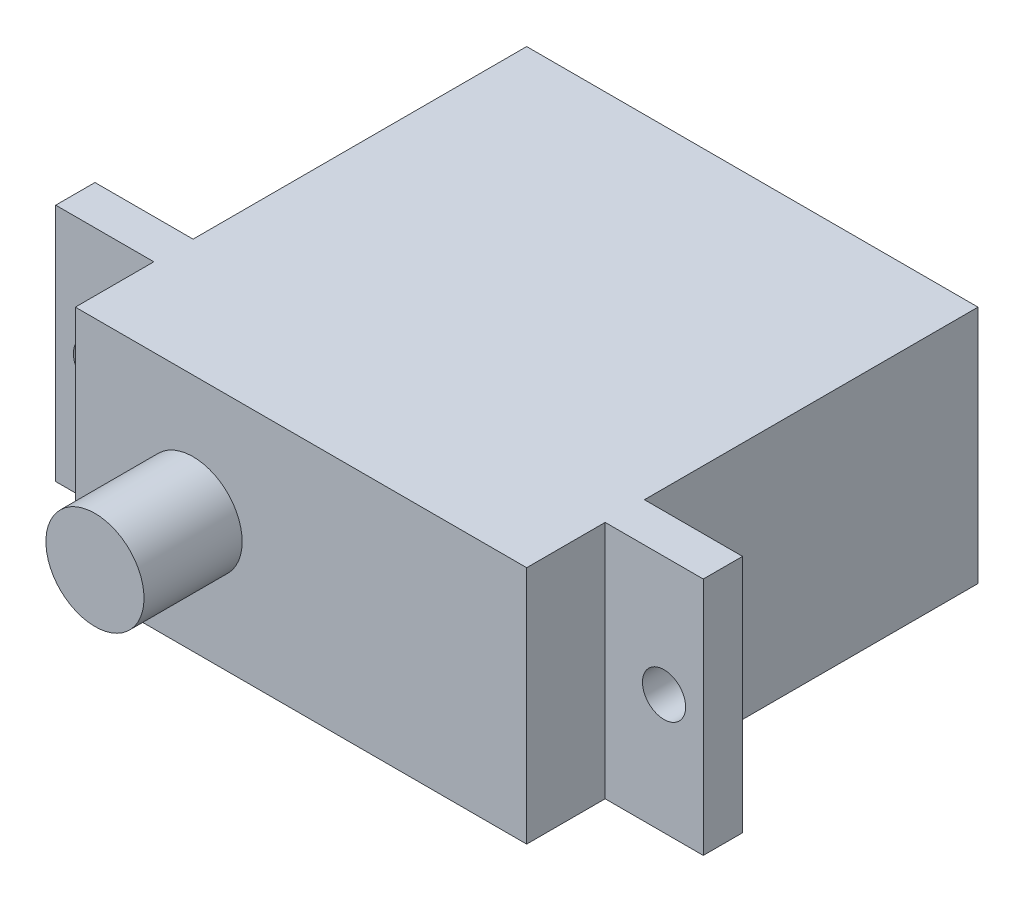
SolidWorks part; units mm, degrees
ref_plane "Front Plane" through (0, 0, 0) normal (0, 0, 1) x (1, 0, 0)
ref_plane "Top Plane" through (0, 0, 0) normal (0, 1, 0) x (1, 0, 0)
ref_plane "Right Plane" through (0, 0, 0) normal (1, 0, 0) x (0, 0, -1)
sketch "Case_23x12p2x23_profile" plane through (0, 0, 0) normal (0, 0, 1) x (1, 0, 0)
  line L1 (-6, -6.1) -> (17, -6.1)
  line L2 (-6, -6.1) -> (-6, 6.1)
  line L3 (-6, 6.1) -> (17, 6.1)
  line L4 (17, -6.1) -> (17, 6.1)
extrude "Case_23x12p2x23" add sketch "Case_23x12p2x23_profile" along normal blind 23 from offset 19
sketch "Mounting_ears_33x12p2_profile" plane through (0, 0, 0) normal (0, 0, 1) x (1, 0, 0)
  line L1 (-11, -6.1) -> (22, -6.1)
  line L2 (-11, -6.1) -> (-11, 6.1)
  line L3 (-11, 6.1) -> (22, 6.1)
  line L4 (22, -6.1) -> (22, 6.1)
extrude "Mounting_ears_33x12p2" add sketch "Mounting_ears_33x12p2_profile" along normal blind 2 from offset 2
sketch "Output_envelope_not_spline_profile" plane through (0, 0, 0) normal (0, 0, 1) x (1, 0, 0)
  circle A0 centre (0, 0) radius 2.5
extrude "Output_envelope_not_spline" add sketch "Output_envelope_not_spline_profile" along normal blind 5 from offset 4
sketch "Mounting_holes_nominal_profile" plane through (0, 0, 0) normal (0, 0, 1) x (1, 0, 0)
  circle A0 centre (-9, 0) radius 1.1
  circle A1 centre (20, 0) radius 1.1
extrude "Mounting_holes_nominal" cut sketch "Mounting_holes_nominal_profile" along normal through all from offset 50
